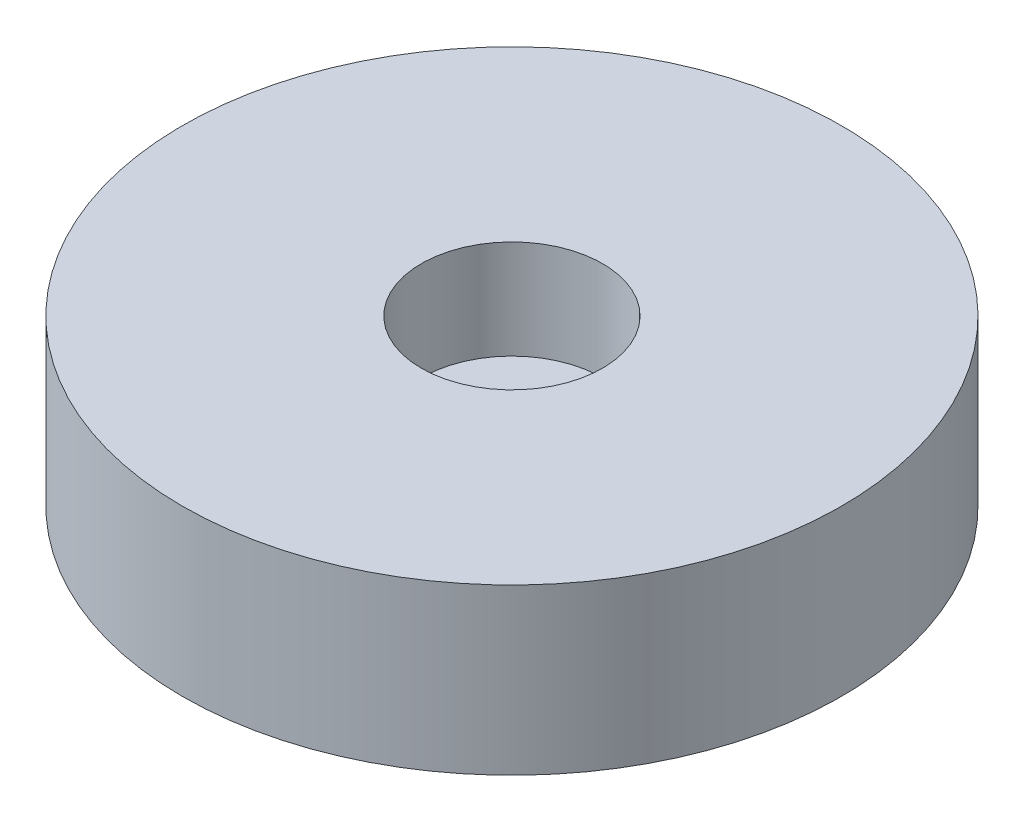
SolidWorks part; units mm, degrees
ref_plane "Front Plane" through (0, 0, 0) normal (0, 0, 1) x (1, 0, 0)
ref_plane "Top Plane" through (0, 0, 0) normal (0, 1, 0) x (1, 0, 0)
ref_plane "Right Plane" through (0, 0, 0) normal (1, 0, 0) x (0, 0, -1)
sketch "Sketch1" plane through (0, 0, 0) normal (0, 1, 0) x (1, 0, 0)
  circle A0 centre (0, 0) radius 6
extrude "Boss-Extrude1" add sketch "Sketch1" along normal blind 3 contours A0
sketch "Sketch2" plane through (0, 3, 0) normal (0, 1, 0) x (1, 0, 0)
  circle A0 centre (0, 0) radius 1.65
extrude "Cut-Extrude1" cut sketch "Sketch2" against normal blind 1.8
